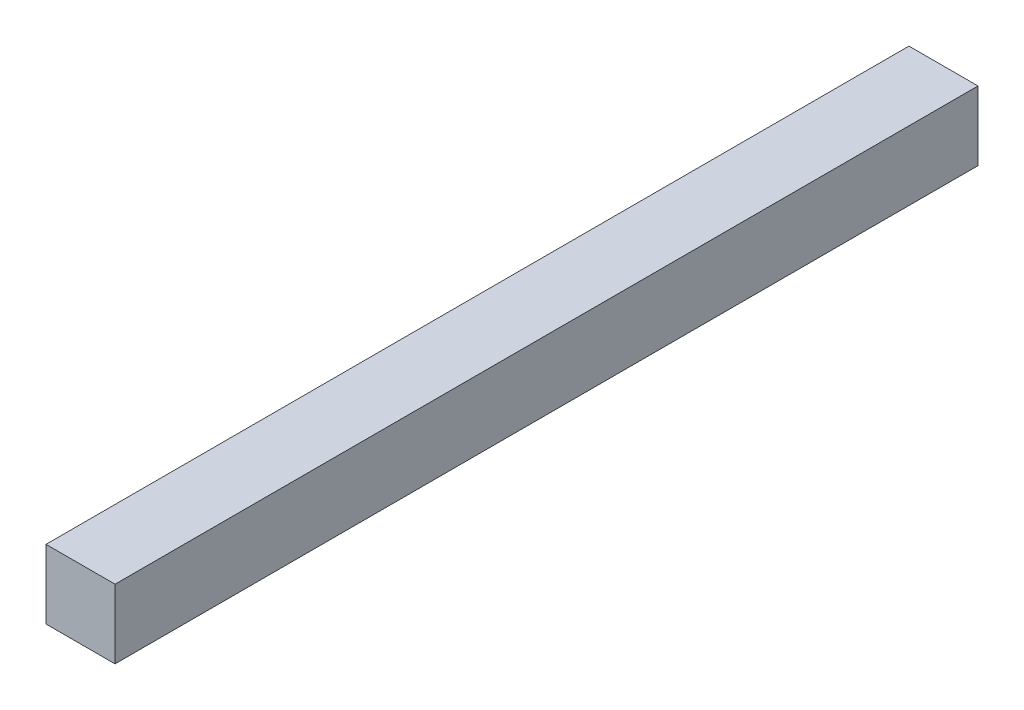
SolidWorks part; units mm, degrees
ref_plane "Front Plane" through (0, 0, 0) normal (0, 0, 1) x (1, 0, 0)
ref_plane "Top Plane" through (0, 0, 0) normal (0, 1, 0) x (1, 0, 0)
ref_plane "Right Plane" through (0, 0, 0) normal (1, 0, 0) x (0, 0, -1)
sketch "Sketch1" plane through (0, 0, 0) normal (0, 0, 1) x (1, 0, 0)
  line L1 (2.4, -2.4) -> (-2.4, -2.4)
  line L2 (2.4, -2.4) -> (2.4, 2.4)
  line L3 (2.4, 2.4) -> (-2.4, 2.4)
  line L4 (-2.4, -2.4) -> (-2.4, 2.4)
  line L5 (2.4, -2.4) -> (-2.4, 2.4) construction
  line L6 (2.4, 2.4) -> (-2.4, -2.4) construction
  point P0 (0, 0)
  dimension "D1" = 4.8
  dimension "D2" = 4.8
extrude "Boss-Extrude1" add sketch "Sketch1" along normal blind 60
